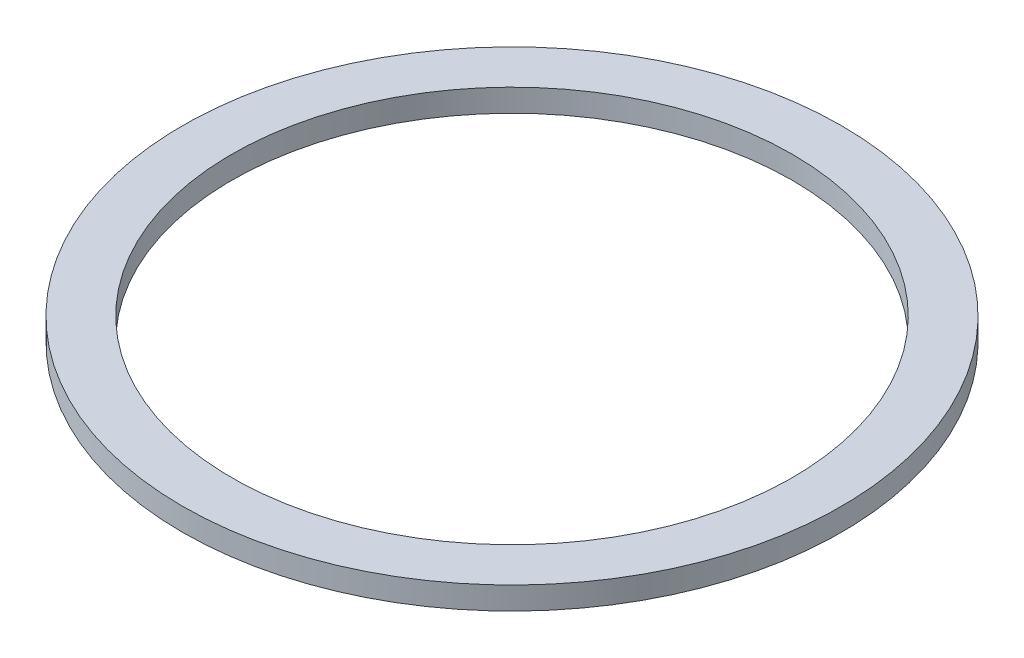
SolidWorks part; units mm, degrees
ref_plane "Front Plane" through (0, 0, 0) normal (0, 0, 1) x (1, 0, 0)
ref_plane "Top Plane" through (0, 0, 0) normal (0, 1, 0) x (1, 0, 0)
ref_plane "Right Plane" through (0, 0, 0) normal (1, 0, 0) x (0, 0, -1)
sketch "Sketch1" plane through (0, 0, 0) normal (0, 1, 0) x (1, 0, 0)
  circle A0 centre (0, 0) radius 18.8976
  circle A1 centre (0, 0) radius 22.225
  dimension "D1" = 37.7952
  dimension "D2" = 44.45
extrude "Boss-Extrude1" add sketch "Sketch1" along normal blind 1.524
